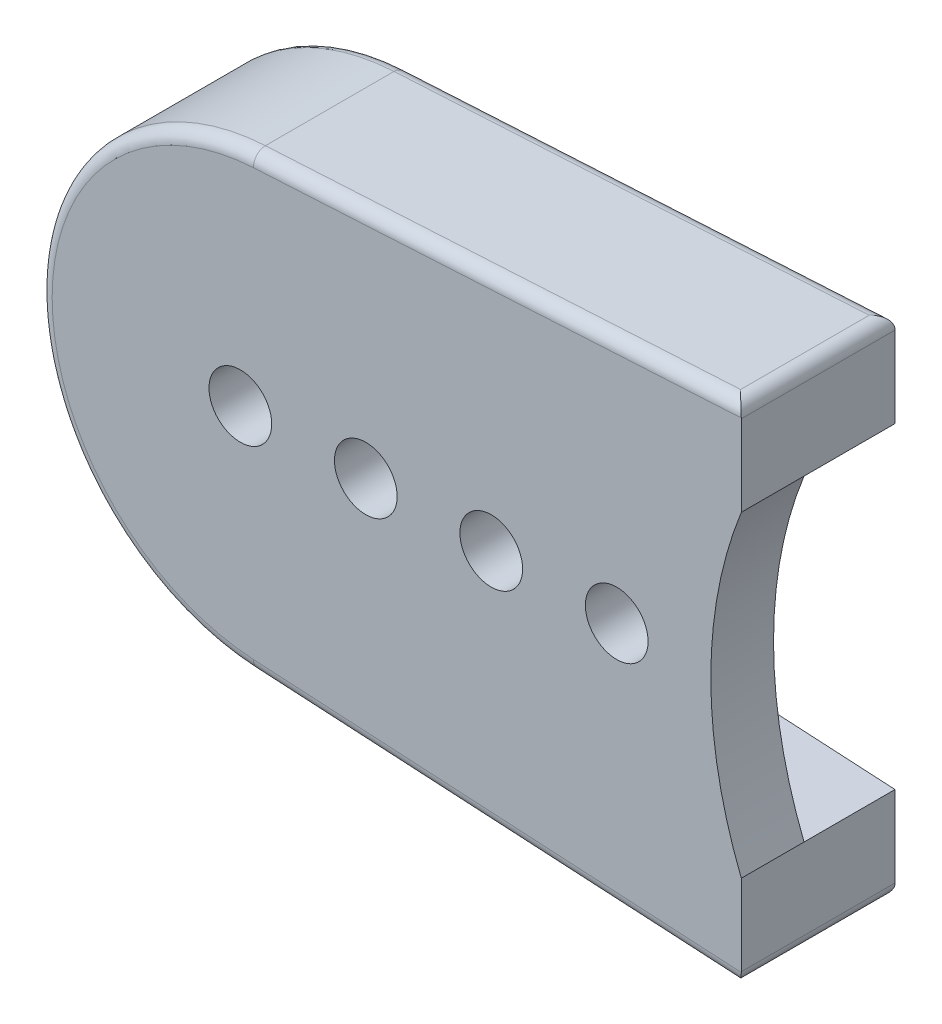
SolidWorks part; units mm, degrees
ref_plane "前视基准面" through (0, 0, 0) normal (0, 0, 1) x (1, 0, 0)
ref_plane "上视基准面" through (0, 0, 0) normal (0, 1, 0) x (1, 0, 0)
ref_plane "右视基准面" through (0, 0, 0) normal (1, 0, 0) x (0, 0, -1)
other "Configuration Table"
sketch "草图1" plane through (0, 0, 0) normal (0, 0, 1) x (1, 0, 0)
  line L10 (-14.0168, -2.0967) -> (-2.2919, -2.7498)
  line L11 (-2.2919, 2.7498) -> (-14.0168, 2.0967)
  line L12 (-14.0168, -2.0967) -> (-6.3135, -2.5258)
  line L13 (-6.3135, 2.5258) -> (-14.0168, 2.0967)
  circle A0 centre (-14.3, 0) radius 0.5 construction
  circle A1 centre (-10.3, 0) radius 0.5 construction
  circle A6 centre (-10.3, 0) radius 0.5
  circle A7 centre (-14.3, 0) radius 0.5
  circle A8 centre (-8.3, 0) radius 0.5 construction
  arc A9 (-14.0168, 2.0967) -> (-14.0168, -2.0967) centre (-13.9, 0) ccw
  arc A10 (-14.0168, 2.0967) -> (-14.0168, -2.0967) centre (-13.9, 0) ccw
  circle A11 centre (-8.3, 0) radius 0.5
  circle A12 centre (-12.3, 0) radius 0.5 construction
  circle A13 centre (-12.3, 0) radius 0.5
  arc A15 (-6.3135, 2.5258) -> (-6.3135, -2.5258) centre (0, 0) ccw
  arc A16 (-2.2864, 2.65) -> (-2.2864, -2.65) centre (0, 0) ccw construction
  circle A17 centre (-6.3, 0) radius 0.5 construction
  dimension "D1" = 0.1
extrude "凸台-拉伸1" add sketch "草图1" along normal blind 1
sketch "草图3" plane through (0, 0, 1) normal (0, 0, 1) x (1, 0, 0)
  line L0 (-6.3135, 4.0282) -> (-14.1002, 3.5944)
  line L1 (-14.1002, -3.5944) -> (-6.3135, -4.0282)
  line L2 (-6.3969, 4.0235) -> (-14.1002, 3.5944) construction
  line L3 (-6.3135, 2.5258) -> (-14.0168, 2.0967)
  line L4 (-14.0168, -2.0967) -> (-6.3135, -2.5258)
  line L6 (-6.3135, 2.5258) -> (-14.0168, 2.0967)
  line L7 (-14.0168, -2.0967) -> (-6.3135, -2.5258)
  line L9 (-14.1002, -3.5944) -> (-6.3969, -4.0235) construction
  line L10 (-6.3135, 2.5258) -> (-6.3135, 4.0282)
  line L11 (-6.3135, -2.5258) -> (-6.3135, -4.0282)
  arc A0 (-14.1002, 3.5944) -> (-14.1002, -3.5944) centre (-13.9, 0) ccw
  arc A1 (-14.0168, 2.0967) -> (-14.0168, -2.0967) centre (-13.9, 0) ccw
  arc A2 (-14.0168, 2.0967) -> (-14.0168, -2.0967) centre (-13.9, 0) ccw
  arc A5 (-6.3135, 2.5258) -> (-6.3135, -2.5258) centre (0, 0) ccw
  arc A6 (-6.3135, 2.5258) -> (-6.3135, -2.5258) centre (0, 0) ccw
  line M5 (-6.3135, 2.5258) -> (-14.0168, 2.0967)
  arc M6 (-14.0168, 2.0967) -> (-14.0168, -2.0967) centre (-13.9, 0) ccw
  line M7 (-14.0168, -2.0967) -> (-6.3135, -2.5258)
  dimension "D1" = 0
  dimension "D2" = 1.5
extrude "凸台-拉伸2" add sketch "草图3" against normal up to surface (2.45 mm away) contours L0 A0 L1 L11 L10 M7 M6 M5
fillet "圆角1" radius 0.2 8 edges at (-10.2069, -3.8113, -1.45) (-10.2069, -3.8113, 1) (-6.3135, -4.0282, -0.225) (-17.5, 0, -1.45) (-17.5, 0, 1) (-10.2069, 3.8113, -1.45) (-10.2069, 3.8113, 1) (-6.3135, 4.0282, -0.225)
